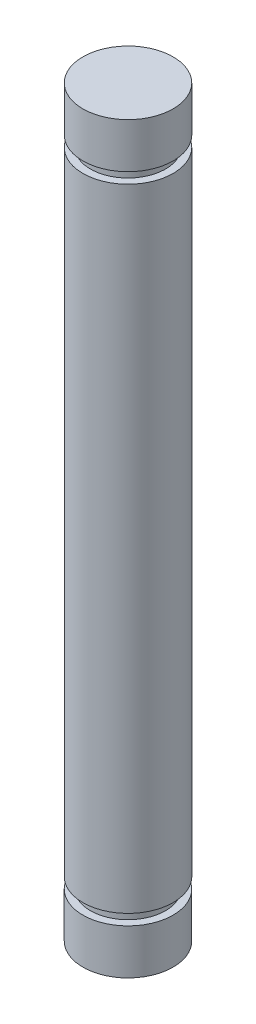
SolidWorks part; units mm, degrees
ref_plane "Front Plane" through (0, 0, 0) normal (0, 0, 1) x (1, 0, 0)
ref_plane "Top Plane" through (0, 0, 0) normal (0, 1, 0) x (1, 0, 0)
ref_plane "Right Plane" through (0, 0, 0) normal (1, 0, 0) x (0, 0, -1)
sketch "Sketch1" plane through (0, 0, 0) normal (0, 1, 0) x (1, 0, 0)
  circle A0 centre (0, 0) radius 3.175
  dimension "D1" = 6.35
extrude "Boss-Extrude1" add sketch "Sketch1" along normal blind 44.45
sketch "Sketch3" plane through (0, 44.45, 0) normal (0, 1, 0) x (1, 0, 0)
  circle A0 centre (0, 0) radius 2.6416
  dimension "D1" = 5.2832
extrude "Boss-Extrude2" add sketch "Sketch3" along normal blind 0.762
sketch "Sketch4" plane through (0, 45.212, 0) normal (0, 1, 0) x (1, 0, 0)
  circle A0 centre (0, 0) radius 3.175
  dimension "D1" = 6.35
extrude "Boss-Extrude3" add sketch "Sketch4" along normal blind 3.175
sketch "Sketch5" plane through (0, 0, 0) normal (0, -1, 0) x (1, 0, 0)
  circle A0 centre (0, 0) radius 2.6416
  dimension "D1" = 5.2832
extrude "Boss-Extrude4" add sketch "Sketch5" along normal blind 0.762
sketch "Sketch6" plane through (0, -0.762, 0) normal (0, -1, 0) x (1, 0, 0)
  circle A0 centre (0, 0) radius 3.175
  dimension "D1" = 6.35
extrude "Boss-Extrude5" add sketch "Sketch6" along normal blind 3.175
